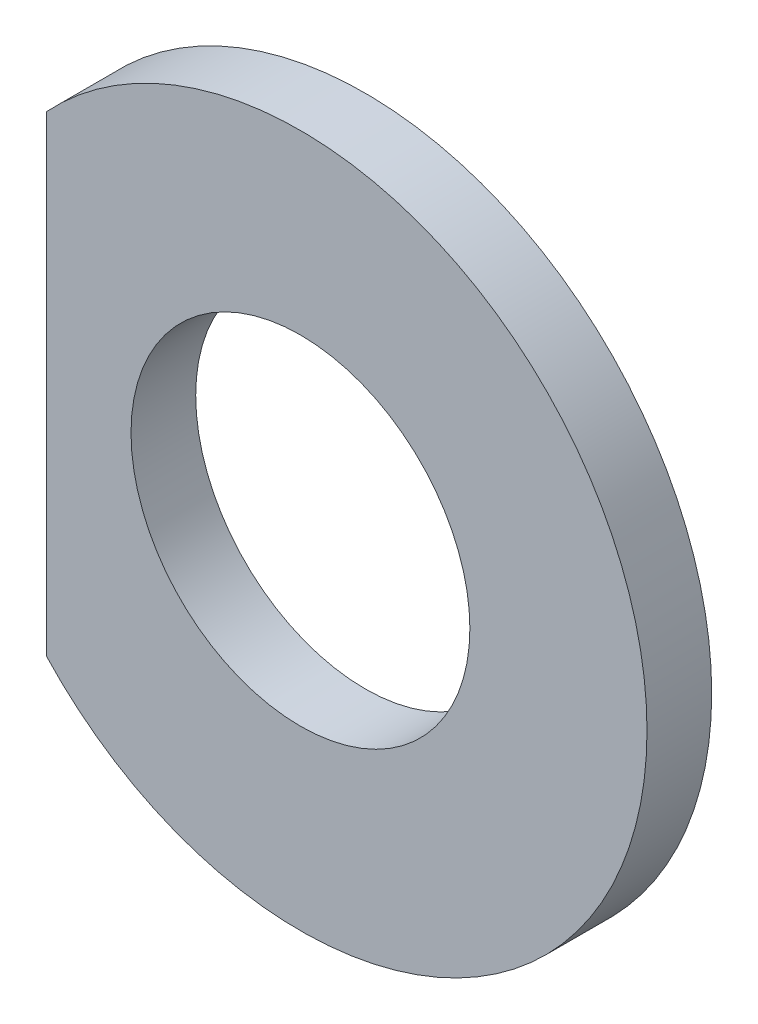
SolidWorks part; units mm, degrees
ref_plane "Front Plane" through (0, 0, 0) normal (0, 0, 1) x (1, 0, 0)
ref_plane "Top Plane" through (0, 0, 0) normal (0, 1, 0) x (1, 0, 0)
ref_plane "Right Plane" through (0, 0, 0) normal (1, 0, 0) x (0, 0, -1)
sketch "Sketch1" plane through (0, 0, 0) normal (0, 0, 1) x (1, 0, 0)
  line L0 (-1.65, 1.5297) -> (-1.65, -1.5297)
  line L1 (0, -2.25) -> (0, 2.25) construction
  line L2 (-1.1, 0) -> (1.1, 0) construction
  circle A0 centre (0, 0) radius 1.1
  arc A1 (-1.65, -1.5297) -> (-1.65, 1.5297) centre (0, 0) ccw
  point P10 (1.1, 0)
  dimension "ID" = 2.2
  dimension "OD" = 4.5
  dimension "B" = 3.9
extrude "Extrude1" add sketch "Sketch1" against normal blind 0.42
